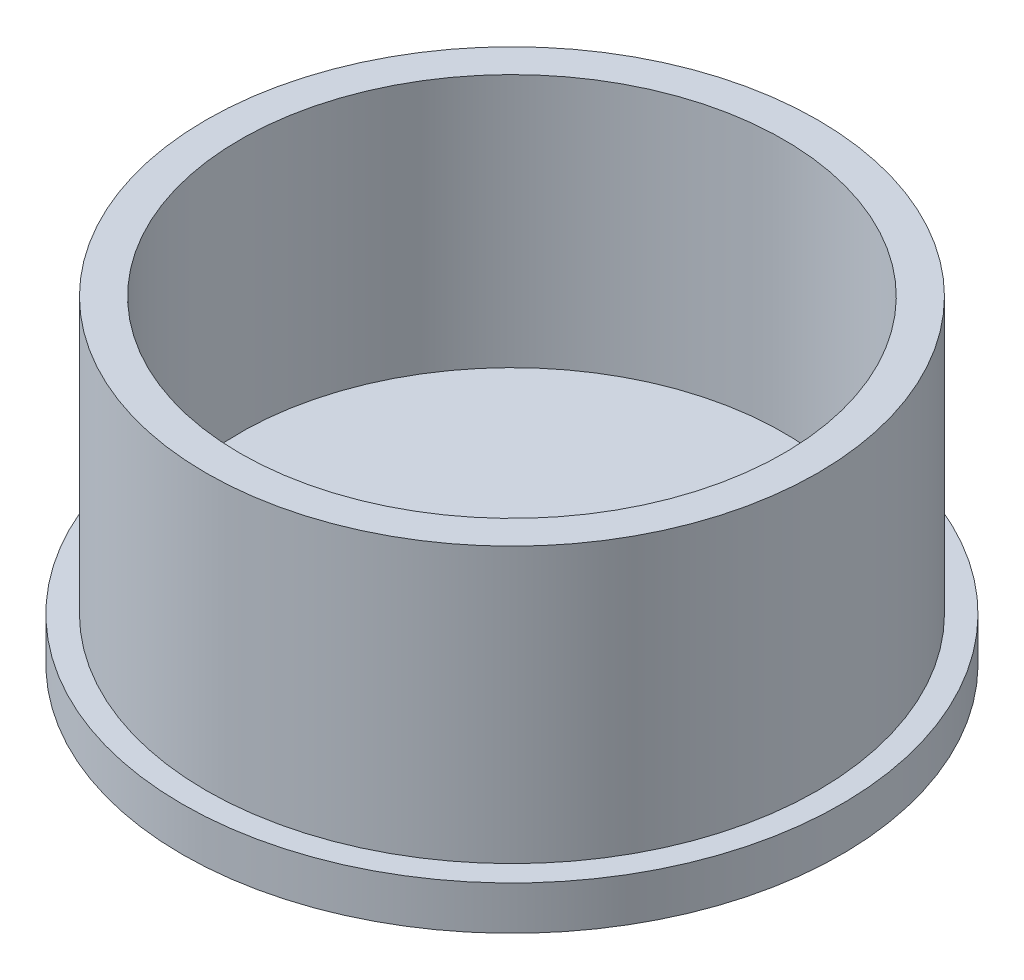
SolidWorks part; units mm, degrees
ref_plane "Front Plane" through (0, 0, 0) normal (0, 0, 1) x (1, 0, 0)
ref_plane "Top Plane" through (0, 0, 0) normal (0, 1, 0) x (1, 0, 0)
ref_plane "Right Plane" through (0, 0, 0) normal (1, 0, 0) x (0, 0, -1)
sketch "Sketch1" plane through (0, 0, 0) normal (0, 1, 0) x (1, 0, 0)
  circle A0 centre (0, 0) radius 11.9062
  dimension "D1" = 23.8125
extrude "Boss-Extrude1" add sketch "Sketch1" along normal blind 1.5748
sketch "Sketch2" plane through (0, 1.5748, 0) normal (0, 1, 0) x (1, 0, 0)
  circle A0 centre (0, 0) radius 11.049
  dimension "D1" = 22.098
extrude "Boss-Extrude2" add sketch "Sketch2" along normal blind 9.9314
sketch "Sketch3" plane through (0, 11.5062, 0) normal (0, 1, 0) x (1, 0, 0)
  circle A0 centre (0, 0) radius 9.8184
extrude "Cut-Extrude1" cut sketch "Sketch3" against normal blind 9.1694
sketch "Sketch4" plane through (0, 11.5062, 0) normal (0, 1, 0) x (1, 0, 0)
  circle A0 centre (0, 0) radius 11.049
